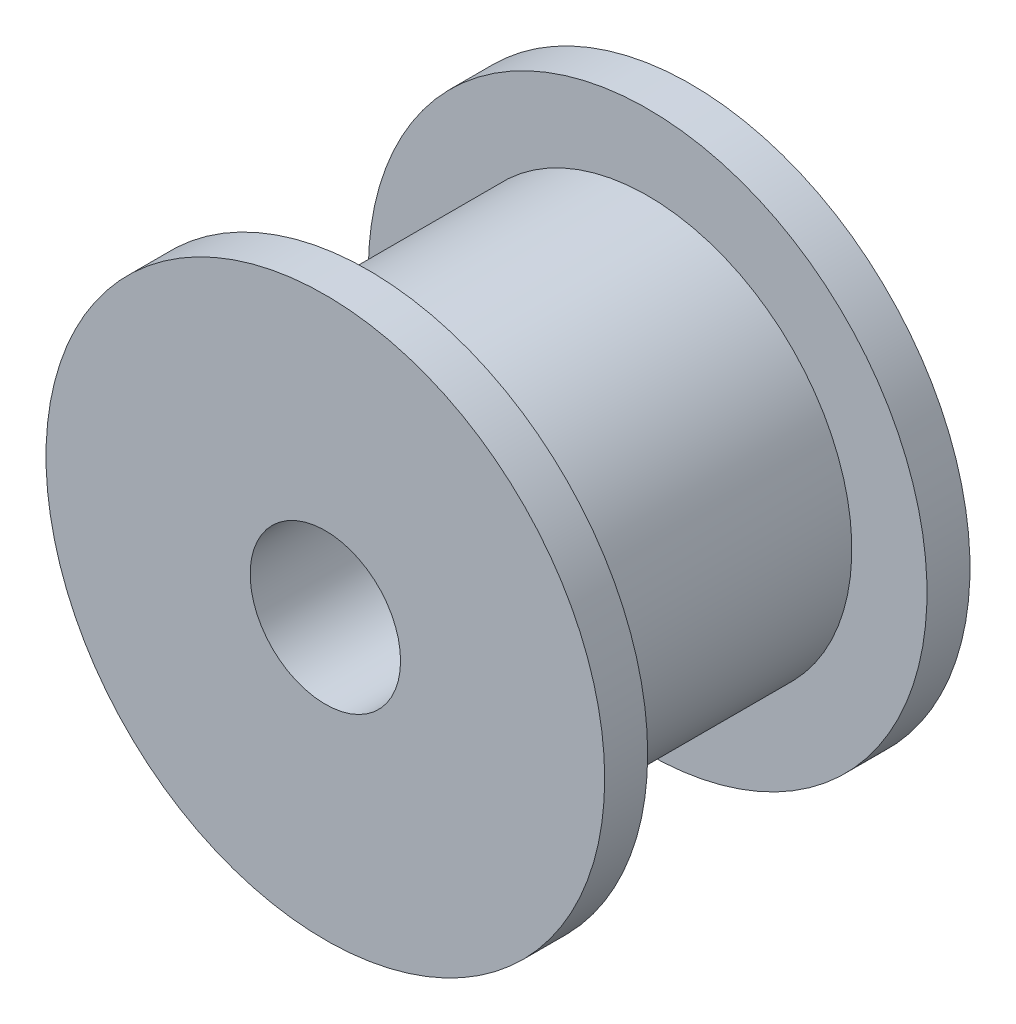
SolidWorks part; units mm, degrees
ref_plane "前视基准面" through (0, 0, 0) normal (0, 0, 1) x (1, 0, 0)
ref_plane "上视基准面" through (0, 0, 0) normal (0, 1, 0) x (1, 0, 0)
ref_plane "右视基准面" through (0, 0, 0) normal (1, 0, 0) x (0, 0, -1)
other "Configuration Table"
sketch "草图1" plane through (0, 0, 0) normal (0, 0, 1) x (1, 0, 0)
  circle A0 centre (0, 0) radius 4.75
  dimension "D1" = 9.5
extrude "凸台-拉伸1" add sketch "草图1" along normal blind 6.5
sketch "草图2" plane through (0, 0, 6.5) normal (0, 0, 1) x (1, 0, 0)
  circle A0 centre (0, 0) radius 6.5
  dimension "D1" = 13
extrude "凸台-拉伸2" add sketch "草图2" along normal blind 1
sketch "草图3" plane through (0, 0, 0) normal (0, 0, -1) x (-1, 0, 0)
  circle A0 centre (0, 0) radius 6.5 construction
  circle A1 centre (0, 0) radius 6.5
extrude "凸台-拉伸3" add sketch "草图3" along normal blind 1
sketch "草图4" plane through (0, 0, 7.5) normal (0, 0, 1) x (1, 0, 0)
  circle A0 centre (0, 0) radius 1.75
  dimension "D1" = 3.5
extrude "切除-拉伸1" cut sketch "草图4" against normal blind 21
